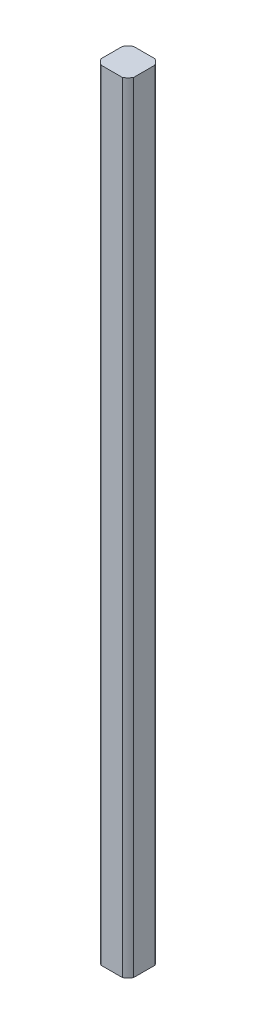
SolidWorks part; units mm, degrees
ref_plane "Front Plane" through (0, 0, 0) normal (0, 0, 1) x (1, 0, 0)
ref_plane "Top Plane" through (0, 0, 0) normal (0, 1, 0) x (1, 0, 0)
ref_plane "Right Plane" through (0, 0, 0) normal (1, 0, 0) x (0, 0, -1)
sketch "Sketch1" plane through (0, 0, 0) normal (0, 1, 0) x (1, 0, 0)
  line L1 (-33.1662, 50) -> (33.1662, 50)
  line L2 (-50, 33.1662) -> (-50, -33.1662)
  line L3 (-33.1662, -50) -> (33.1662, -50)
  line L4 (50, 33.1662) -> (50, -33.1662)
  line L5 (-42.4264, 42.4264) -> (42.4264, -42.4264) construction
  line L6 (-42.4264, -42.4264) -> (42.4264, 42.4264) construction
  arc A0 (-33.1662, 50) -> (-50, 33.1662) centre (0, 0) ccw
  arc A1 (50, 33.1662) -> (33.1662, 50) centre (0, 0) ccw
  arc A2 (33.1662, -50) -> (50, -33.1662) centre (0, 0) ccw
  arc A3 (-50, -33.1662) -> (-33.1662, -50) centre (0, 0) ccw
  dimension "D1" = 120
extrude "Boss-Extrude1" add sketch "Sketch1" along normal blind 2400
